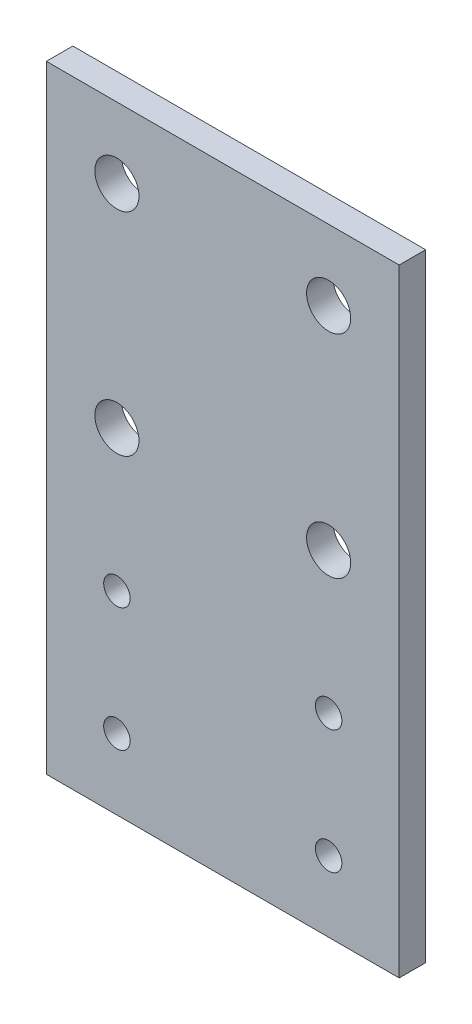
SolidWorks part; units mm, degrees
material "Thornel Mat VMA"
ref_plane "Front" through (0, 0, 0) normal (0, 0, 1) x (1, 0, 0)
ref_plane "Top" through (0, 0, 0) normal (0, 1, 0) x (1, 0, 0)
ref_plane "Right" through (0, 0, 0) normal (1, 0, 0) x (0, 0, -1)
sketch "草图1" plane through (0, 0, 0) normal (0, 0, 1) x (1, 0, 0)
  line L0 (-20, 35) -> (0, 70)
  line L1 (-20, -35) -> (20, -35)
  line L2 (-20, -35) -> (-20, 35)
  line L3 (-20, 35) -> (20, 35) construction
  line L4 (20, -35) -> (20, 35)
  line L5 (-20, -35) -> (20, 35) construction
  line L6 (-20, 35) -> (20, -35) construction
  line L7 (0, 70) -> (20, 70)
  line L8 (20, 70) -> (20, 35)
  point P0 (0, 0)
  dimension "D1" = 40
  dimension "D2" = 70
  dimension "D3" = 35
  dimension "D4" = 20
extrude "凸台-拉伸1" add sketch "草图1" along normal blind 3
sketch "草图2" plane through (0, 0, 3) normal (0, 0, 1) x (1, 0, 0)
  line L1 (6, 61) -> (17, 61) construction
  line L2 (4.8512, 41) -> (17, 41) construction
  line L3 (17, 61) -> (17, 41) construction
  line L4 (20, -35) -> (20, 70) construction
  line L5 (-20, -35) -> (20, -35) construction
  circle A0 centre (17, 61) radius 1.55
  circle A1 centre (6, 61) radius 1.55
  circle A2 centre (17, 41) radius 1.55
  circle A3 centre (4.8512, 41) radius 1.55
  dimension "D1" = 3.1
  dimension "D2" = 76
  dimension "D3" = 3.1
  dimension "D4" = 11
  dimension "D5" = 20
  dimension "D6" = 3
extrude "切除-拉伸1" cut sketch "草图2" against normal through all
sketch "草图3" plane through (0, 0, 3) normal (0, 0, 1) x (1, 0, 0)
  line L0 (-20, -35) -> (20, -35) construction
  line L1 (20, -35) -> (20, 70) construction
  line L2 (-20, 35) -> (-20, -35) construction
  line L3 (-12, -13) -> (12, -13) construction
  line L4 (12, -13) -> (12, -27) construction
  line L5 (12, -27) -> (-12, -27) construction
  line L6 (-12, -27) -> (-12, -13) construction
  line L7 (-12, 27) -> (12, 27) construction
  line L8 (12, 27) -> (12, 3) construction
  line L9 (12, 3) -> (-12, 3) construction
  line L10 (-12, 3) -> (-12, 27) construction
  circle A0 centre (12, -27) radius 1.5
  circle A1 centre (-12, -27) radius 1.5
  circle A2 centre (12, -13) radius 1.5
  circle A3 centre (-12, -13) radius 1.5
  circle A4 centre (12, 3) radius 2.5
  circle A5 centre (-12, 3) radius 2.5
  circle A6 centre (12, 27) radius 2.5
  circle A7 centre (-12, 27) radius 2.5
  dimension "D1" = 3
  dimension "D2" = 8
  dimension "D3" = 8
  dimension "D4" = 3
  dimension "D5" = 8
  dimension "D6" = 8
  dimension "D7" = 22
  dimension "D8" = 5
  dimension "D9" = 5
  dimension "D14" = 3
  dimension "D15" = 3
  dimension "D10" = 8
  dimension "D11" = 8
  dimension "D12" = 38
  dimension "D13" = 8
extrude "切除-拉伸2" cut sketch "草图3" against normal through all
sketch "草图4" plane through (0, 0, 0) normal (0, 0, -1) x (-1, 0, 0)
  line L1 (20, 35) -> (-20, 35)
  line L2 (20, 35) -> (20, 70)
  line L3 (20, 70) -> (-20, 70)
  line L4 (-20, 35) -> (-20, 70)
extrude "切除-拉伸3" cut sketch "草图4" against normal through all
